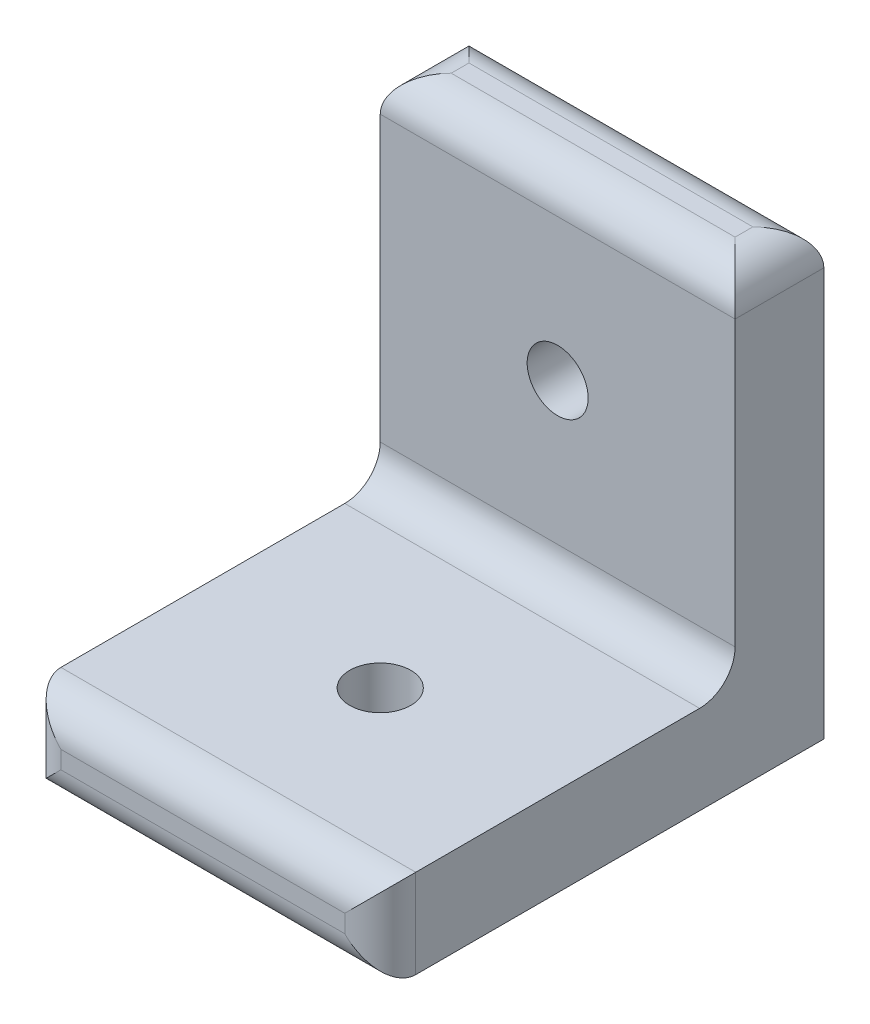
SolidWorks part; units mm, degrees
ref_plane "Front Plane" through (0, 0, 0) normal (0, 0, 1) x (1, 0, 0)
ref_plane "Top Plane" through (0, 0, 0) normal (0, 1, 0) x (1, 0, 0)
ref_plane "Right Plane" through (0, 0, 0) normal (1, 0, 0) x (0, 0, -1)
sketch "Sketch1" plane through (0, 0, 0) normal (0, 1, 0) x (1, 0, 0)
  line L1 (-12.7, -12.7) -> (12.7, -12.7)
  line L2 (-12.7, -12.7) -> (-12.7, 12.7)
  line L3 (-12.7, 12.7) -> (12.7, 12.7)
  line L4 (12.7, -12.7) -> (12.7, 12.7)
  line L5 (-12.7, -12.7) -> (12.7, 12.7) construction
  line L6 (-12.7, 12.7) -> (12.7, -12.7) construction
  point P0 (0, 0)
  dimension "D1" = 25.4
  dimension "D2" = 25.4
extrude "Boss-Extrude1" add sketch "Sketch1" along normal blind 6.35
sketch "Sketch2" plane through (0, 0, -12.7) normal (0, 0, -1) x (-1, 0, 0)
  line L1 (-12.7, 31.75) -> (12.7, 31.75)
  line L2 (-12.7, 31.75) -> (-12.7, 0)
  line L3 (-12.7, 0) -> (12.7, 0)
  line L4 (12.7, 31.75) -> (12.7, 0)
  line L5 (-12.7, 31.75) -> (12.7, 0) construction
  line L6 (-12.7, 0) -> (12.7, 31.75) construction
  point P0 (0, 15.875)
  dimension "D1" = 31.75
  dimension "D2" = 25.4
extrude "Boss-Extrude2" add sketch "Sketch2" along normal blind 6.35
fillet "Fillet1" radius 2.54 9 edges at (-12.7, 31.75, -15.875) (12.7, 31.75, -15.875) (-12.7, 3.175, 12.7) (12.7, 3.175, 12.7) (0, 31.75, -19.05) (0, 31.75, -12.7) (0, 0, 12.7) (0, 6.35, 12.7) (0, 6.35, -12.7)
sketch "Sketch3" plane through (0, 6.35, 0) normal (0, 1, 0) x (1, 0, 0)
  line L0 (-12.7, 10.16) -> (-12.7, -10.16) construction
  line L1 (10.16, -12.7) -> (-10.16, -12.7) construction
  point P0 (0, 0)
sketch "Sketch4" plane through (0, 0, -12.7) normal (0, 0, 1) x (1, 0, 0)
  line L0 (-12.7, 8.89) -> (12.7, 8.89) construction
  point P0 (0, 19.05)
  dimension "D1" = 10.16
hole_wizard "11/64 (0.17188) Diameter Hole1" positions "Sketch5" profile "Sketch6" hole size "11/64" standard "ANSI Inch" end condition through all
sketch "Sketch5" plane through (0, 6.35, 0) normal (0, 1, 0) x (1, 0, 0)
  point P0 (0, 0)
sketch "Sketch6" plane through (0, 6.35, 0) normal (1, 0, 0) x (0, 0, 1)
  line L0 (0, 0) -> (0, 6.35)
  line L1 (0, 6.35) -> (2.1829, 6.35)
  line L2 (2.1829, 6.35) -> (2.1829, 0)
  line L5 (2.1829, 0) -> (0, 0)
  line L11 (0, -6.35) -> (0, 107.95) construction
  dimension "Thru Hole Dia." = 4.3658
  dimension "Thru Hole Depth" = 6.35
hole_wizard "11/64 (0.17188) Diameter Hole2" positions "Sketch7" profile "Sketch8" hole size "11/64" standard "ANSI Inch" end condition through all
sketch "Sketch7" plane through (0, 0, -12.7) normal (0, 0, 1) x (1, 0, 0)
  point P0 (0, 19.05)
sketch "Sketch8" plane through (0, 19.05, -12.7) normal (1, 0, 0) x (0, -1, 0)
  line L0 (0, 0) -> (0, 6.35)
  line L1 (0, 6.35) -> (2.1829, 6.35)
  line L2 (2.1829, 6.35) -> (2.1829, 0)
  line L5 (2.1829, 0) -> (0, 0)
  line L11 (0, -6.35) -> (0, 107.95) construction
  dimension "Thru Hole Dia." = 4.3658
  dimension "Thru Hole Depth" = 6.35
